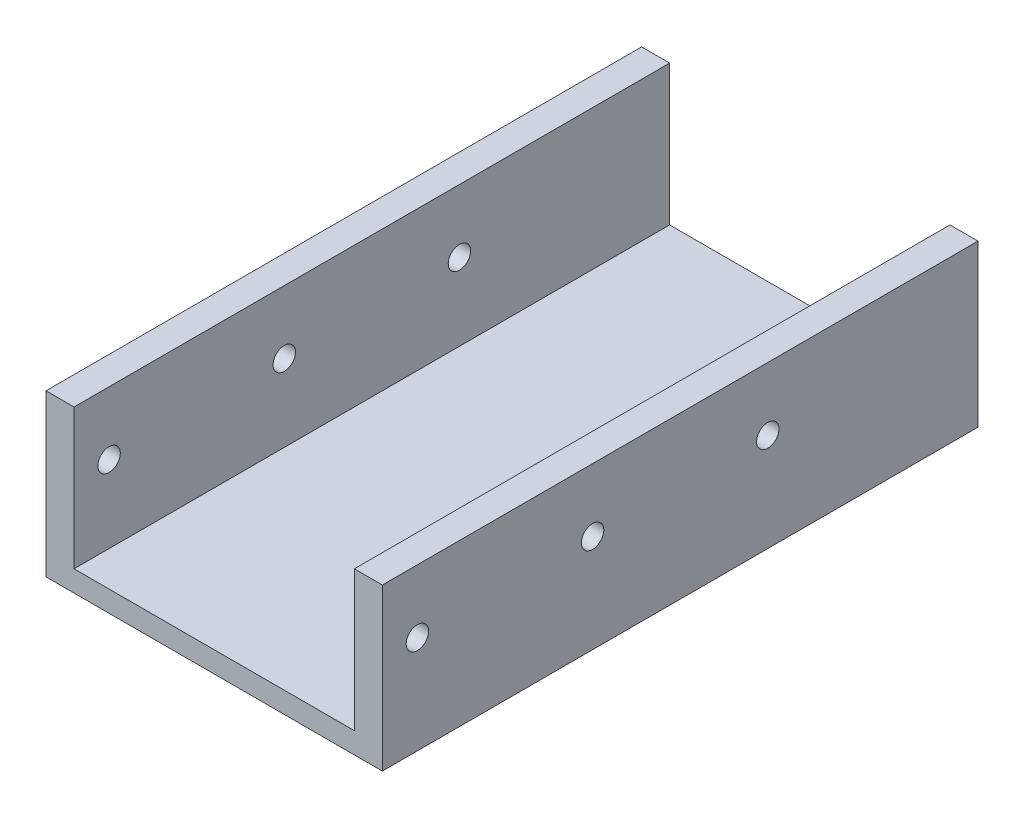
SolidWorks part; units mm, degrees
material "PLA"
ref_plane "前视基准面" through (0, 0, 0) normal (0, 0, 1) x (1, 0, 0)
ref_plane "上视基准面" through (0, 0, 0) normal (0, 1, 0) x (1, 0, 0)
ref_plane "右视基准面" through (0, 0, 0) normal (1, 0, 0) x (0, 0, -1)
sketch "草图2" plane through (0, 0, 0) normal (0, 1, 0) x (1, 0, 0)
  line L1 (-24, -55) -> (24, -55)
  line L2 (-24, -55) -> (-24, 55)
  line L3 (-24, 55) -> (24, 55)
  line L4 (24, -55) -> (24, 55)
  line L5 (-24, -55) -> (24, 55) construction
  line L6 (-24, 55) -> (24, -55) construction
  point P0 (0, 0)
  dimension "D1" = 48
  dimension "D2" = 110
extrude "凸台-拉伸1" add sketch "草图2" along normal blind 3
sketch "草图3" plane through (0, 3, 0) normal (0, 1, 0) x (1, 0, 0)
  line L0 (-24, -55) -> (24, -55) construction
  line L1 (-24, 55) -> (-20, 55)
  line L2 (-24, 55) -> (-24, -55)
  line L3 (-24, -55) -> (-20, -55)
  line L4 (-20, 55) -> (-20, -55)
  line L5 (0, 55) -> (0, -55) construction
  line L10 (24, 55) -> (-24, 55) construction
  line L11 (24, -55) -> (20, -55)
  line L12 (20, 55) -> (20, -55)
  line L13 (24, 55) -> (20, 55)
  line L14 (24, 55) -> (24, -55)
  dimension "D1" = 4
extrude "凸台-拉伸2" add sketch "草图3" along normal blind 20
sketch "草图4" plane through (-24, 0, 0) normal (-1, 0, 0) x (0, 0, 1)
  line L0 (-40, 14) -> (40, 14) construction
  line L3 (0, 23) -> (0, 0) construction
  line L4 (-55, 23) -> (55, 23) construction
  line L5 (55, 3) -> (-55, 3) construction
  circle A0 centre (0, 14) radius 1.6
  circle A1 centre (-25, 14) radius 1.6
  circle A2 centre (25, 14) radius 1.6
  dimension "D1" = 3.2
  dimension "D2" = 3.2
  dimension "D3" = 25
  dimension "D4" = 11
extrude "切除-拉伸1" cut sketch "草图4" against normal through all
sketch "草图5" plane through (24, 0, 0) normal (1, 0, 0) x (0, 0, -1)
  line L5 (-55, 0) -> (55, 0) construction
  line L6 (-55, 23) -> (-30, 23)
  line L7 (-55, 23) -> (-55, 0)
  line L8 (-55, 0) -> (-30, 0)
  line L9 (-30, 23) -> (-30, 0)
  dimension "D1" = 25
extrude "切除-拉伸2" cut sketch "草图5" against normal through all
